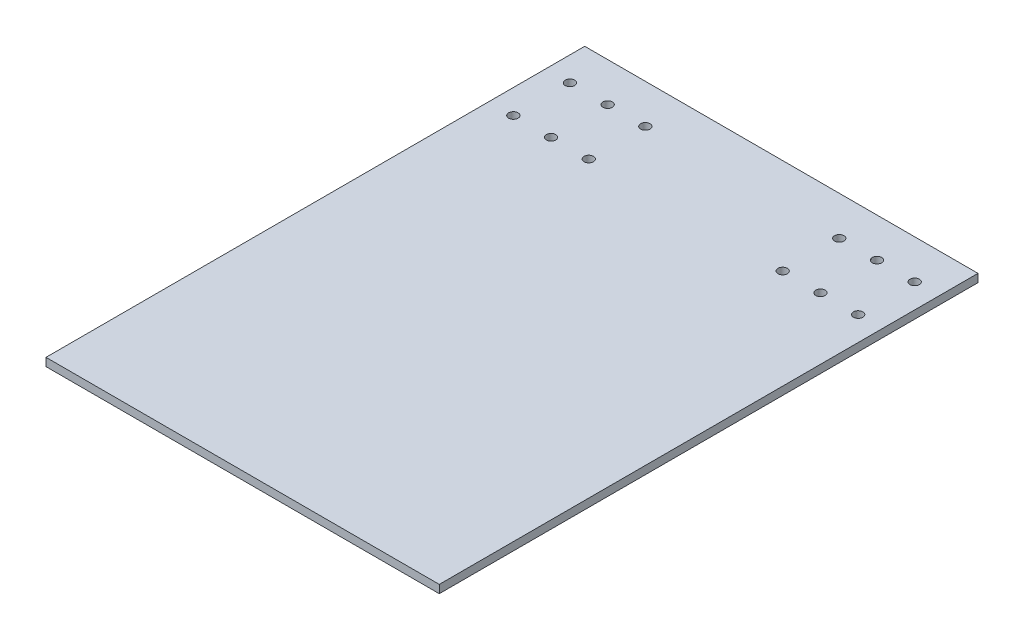
SolidWorks part; units mm, degrees
ref_plane "Front Plane" through (0, 0, 0) normal (0, 0, 1) x (1, 0, 0)
ref_plane "Top Plane" through (0, 0, 0) normal (0, 1, 0) x (1, 0, 0)
ref_plane "Right Plane" through (0, 0, 0) normal (1, 0, 0) x (0, 0, -1)
sketch "Sketch1" plane through (0, 0, 0) normal (0, 1, 0) x (1, 0, 0)
  line L0 (-73, 75) -> (-19.8296, 75) construction
  line L1 (-73, -100) -> (73, -100)
  line L2 (-73, -100) -> (-73, 100)
  line L3 (-73, 100) -> (73, 100)
  line L4 (73, -100) -> (73, 100)
  line L5 (-73, -100) -> (73, 100) construction
  line L6 (-73, 100) -> (73, -100) construction
  line L7 (0, 0) -> (0, 38.8703) construction
  circle A0 centre (-64, 85.5) radius 1.75
  circle A1 centre (-64, 64.5) radius 1.75
  circle A2 centre (-50, 85.5) radius 1.75
  circle A3 centre (-50, 64.5) radius 1.75
  circle A4 centre (-36, 85.5) radius 1.75
  circle A5 centre (-36, 64.5) radius 1.75
  circle A6 centre (36, 64.5) radius 1.75
  circle A7 centre (36, 85.5) radius 1.75
  circle A8 centre (50, 64.5) radius 1.75
  circle A9 centre (50, 85.5) radius 1.75
  circle A10 centre (64, 64.5) radius 1.75
  circle A11 centre (64, 85.5) radius 1.75
  point P0 (0, 0)
  dimension "D3" = 3.5
  dimension "D1" = 146
  dimension "D2" = 200
  dimension "D4" = 10.5
  dimension "D5" = 9
  dimension "D7" = 14
  dimension "D8" = 25
  dimension "D9" = 10.5
  dimension "D6" = 3
extrude "Boss-Extrude1" add sketch "Sketch1" along normal blind 3
